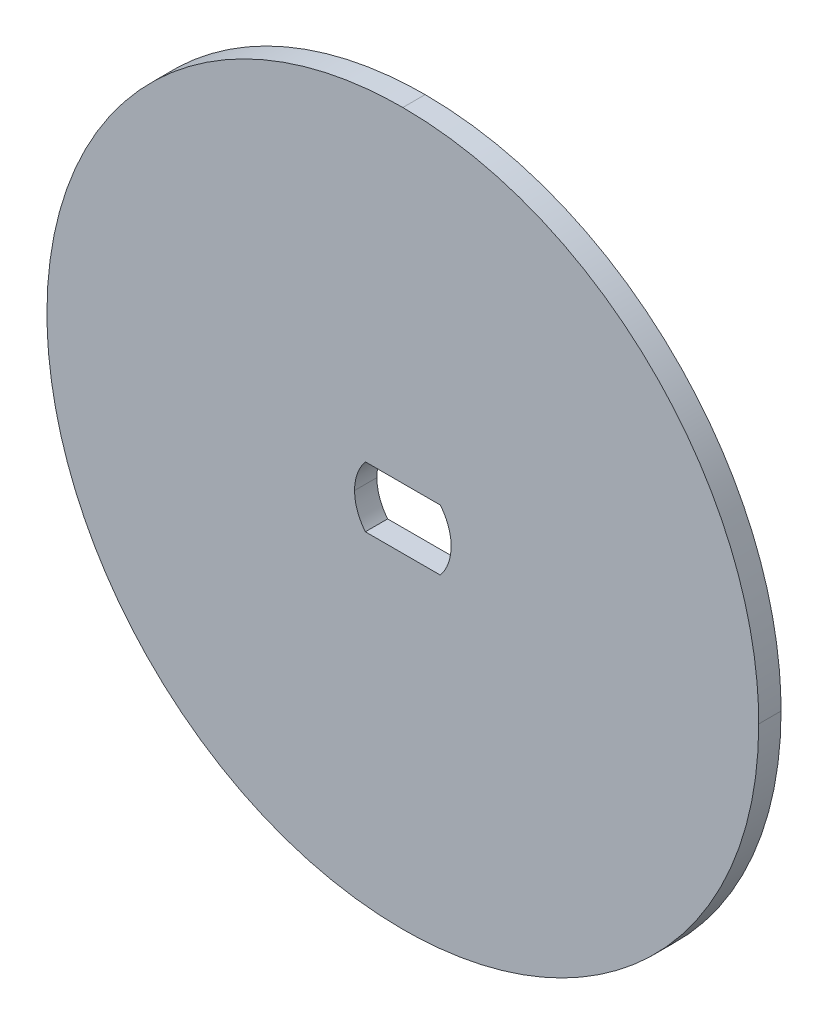
SolidWorks part; units mm, degrees
ref_plane "Front Plane" through (0, 0, 0) normal (0, 0, 1) x (1, 0, 0)
ref_plane "Top Plane" through (0, 0, 0) normal (0, 1, 0) x (1, 0, 0)
ref_plane "Right Plane" through (0, 0, 0) normal (1, 0, 0) x (0, 0, -1)
sketch "retainer" plane through (0, 0, 0) normal (0, 0, 1) x (1, 0, 0)
  line L819 (47.345, 153.121) -> (52.6807, 153.121)
  line L820 (52.6807, 153.121) -> (47.345, 153.121)
  line L821 (52.6807, 157.4337) -> (47.345, 157.4337)
  line L822 (47.345, 157.4337) -> (52.6807, 157.4337)
  spline S88 degree 3 poles (75.331, 155.2774) (75.331, 141.2945) (63.9956, 129.9592) (50.0128, 129.9592) knots 0 0 0 0 1 1 1 1
  spline S89 degree 3 poles (50.0128, 129.9592) (36.03, 129.9592) (24.6947, 141.2945) (24.6947, 155.2774) knots 0 0 0 0 1 1 1 1
  spline S90 degree 3 poles (24.6947, 155.2774) (24.6947, 169.2602) (36.03, 180.5955) (50.0128, 180.5955) knots 0 0 0 0 1 1 1 1
  spline S91 degree 3 poles (50.0128, 180.5955) (63.9956, 180.5955) (75.331, 169.2602) (75.331, 155.2774) knots 0 0 0 0 1 1 1 1
  spline S92 degree 3 poles (47.345, 157.4337) (46.8673, 156.8439) (46.5777, 156.0999) (46.5777, 155.2818) knots 0 0 0 0 1 1 1 1
  spline S93 degree 3 poles (46.5777, 155.2818) (46.5777, 154.4636) (46.8673, 153.7108) (47.345, 153.121) knots 0 0 0 0 1 1 1 1
  spline S94 degree 3 poles (52.6807, 153.121) (53.1584, 153.7108) (53.448, 154.4636) (53.448, 155.2818) knots 0 0 0 0 1 1 1 1
  spline S95 degree 3 poles (53.448, 155.2818) (53.448, 156.0999) (53.1584, 156.8439) (52.6807, 157.4337) knots 0 0 0 0 1 1 1 1
extrude "Boss-Extrude6" add sketch "retainer" along normal blind 1.5875 separate body contours S91 S90 S89 S88 S95 S94 L819 S93 S92 L821
